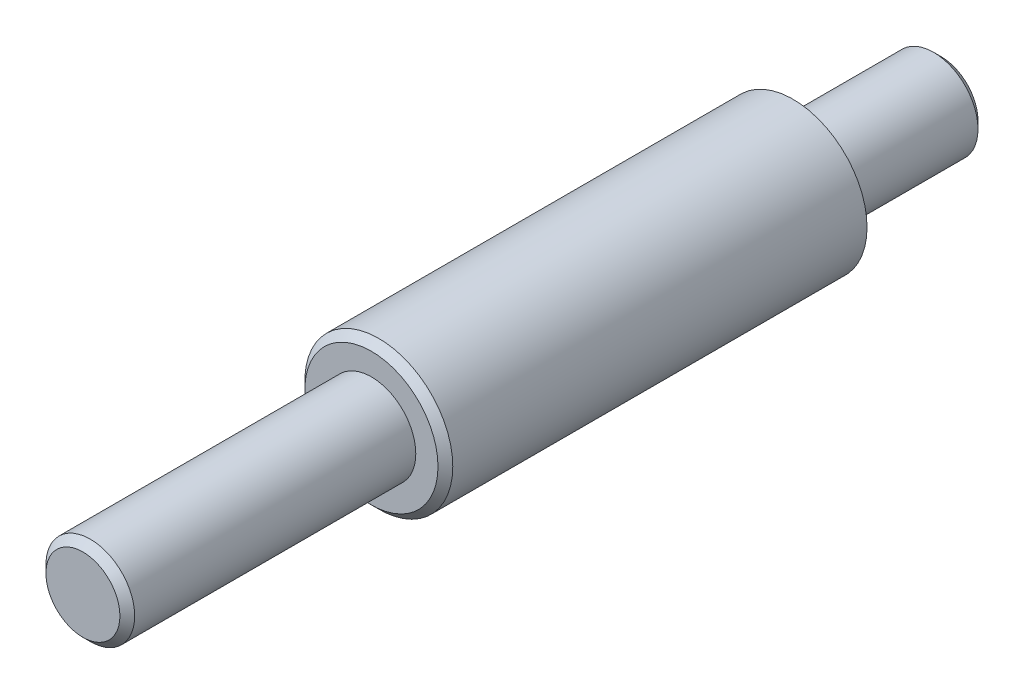
SolidWorks part; units mm, degrees
material "1.7225 (42CrMo4)"
ref_plane "Front Plane" through (0, 0, 0) normal (0, 0, 1) x (1, 0, 0)
ref_plane "Top Plane" through (0, 0, 0) normal (0, 1, 0) x (1, 0, 0)
ref_plane "Right Plane" through (0, 0, 0) normal (1, 0, 0) x (0, 0, -1)
sketch "Sketch1" plane through (0, 0, 0) normal (0, 1, 0) x (1, 0, 0)
  line L0 (2.5, 0) -> (0, 0)
  line L1 (0, 0) -> (0, -58)
  line L2 (0, -58) -> (2.5, -58)
  line L3 (2.5, -58) -> (3, -57.5)
  line L4 (3, -57.5) -> (3, -38.5)
  line L5 (3, -38.5) -> (4.5, -38.5)
  line L6 (4.5, -38.5) -> (5, -38)
  line L7 (5, -38) -> (5, -10)
  line L8 (5, -10) -> (3, -10)
  line L9 (3, -10) -> (3, -0.5)
  line L10 (3, -0.5) -> (2.5, 0)
  line L11 (0, 0) -> (0, -58) construction
  dimension "D1" = 2.5
  dimension "D2" = 3
  dimension "D3" = 4.5
  dimension "D4" = 5
  dimension "D5" = 0.5
  dimension "D6" = 19.5
  dimension "D7" = 20
  dimension "D8" = 48
  dimension "D9" = 57.5
  dimension "D10" = 58
  dimension "D11" = 2.5
  dimension "D12" = 58
revolve "Revolve1" add sketch "Sketch1" angle 360 about L11
